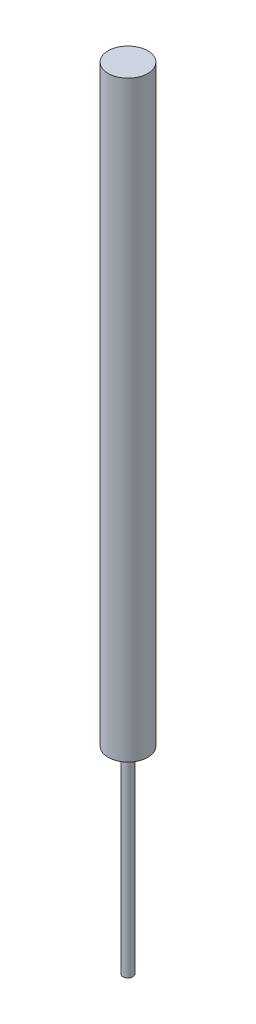
SolidWorks part; units mm, degrees
ref_plane "Front Plane" through (0, 0, 0) normal (0, 0, 1) x (1, 0, 0)
ref_plane "Top Plane" through (0, 0, 0) normal (0, 1, 0) x (1, 0, 0)
ref_plane "Right Plane" through (0, 0, 0) normal (1, 0, 0) x (0, 0, -1)
sketch "Sketch1" plane through (0, 0, 0) normal (0, 1, 0) x (1, 0, 0)
  circle A0 centre (0, 0) radius 0.25
  dimension "D1" = 0.5
extrude "Boss-Extrude1" add sketch "Sketch1" along normal blind 10
sketch "Sketch2" plane through (0, 10, 0) normal (0, 1, 0) x (1, 0, 0)
  circle A0 centre (0, 0) radius 1
  dimension "D1" = 2
extrude "Boss-Extrude2" add sketch "Sketch2" along normal blind 30
